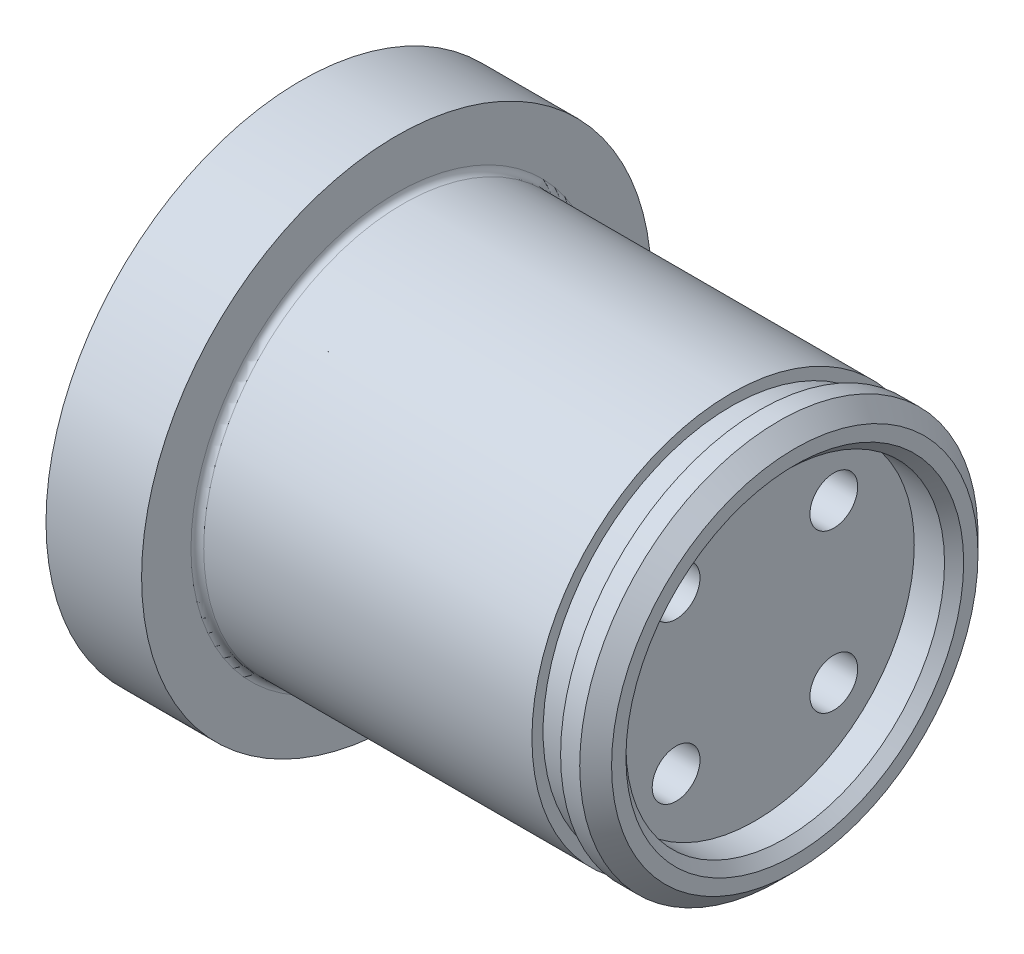
SolidWorks part; units mm, degrees
material "1060 Сплав"
ref_plane "Спереди" through (0, 0, 0) normal (0, 0, 1) x (1, 0, 0)
ref_plane "Сверху" through (0, 0, 0) normal (0, 1, 0) x (1, 0, 0)
ref_plane "Справа" through (0, 0, 0) normal (1, 0, 0) x (0, 0, -1)
sketch "Эскиз1" plane through (0, 0, 0) normal (0, 0, 1) x (1, 0, 0)
  line L0 (0, 0) -> (22138.4448, 0) construction
  line L1 (0, 0) -> (0, 12.5)
  line L2 (0, 12.5) -> (-25, 12.5)
  line L3 (-25, 12.5) -> (-25, 16)
  line L4 (-25, 16) -> (-31, 16)
  line L5 (-31, 16) -> (-31, 0)
  line L8 (0, 0) -> (-31, 0)
  dimension "D1" = 31
  dimension "D2" = 6
  dimension "D3" = 25
  dimension "D6" = 32
revolve "Повернуть1" add sketch "Эскиз1" angle 360 about L0
sketch "Эскиз2" plane through (0, 0, 0) normal (0, 0, 1) x (1, 0, 0)
  line L0 (-4, 12.5) -> (-4, 11.8)
  line L1 (0, 12.5) -> (-25, 12.5) construction
  line L2 (-4, 11.8) -> (-2.2, 11.8)
  line L3 (-2.2, 11.8) -> (-2.2, 12.5)
  line L4 (-2.2, 12.5) -> (-4, 12.5)
  line L5 (0, -12.5) -> (0, 12.5) construction
  line L6 (0, 0) -> (-50000, 0) construction
  point P10 (-2.2, 12.15)
  point P13 (0, 0)
  dimension "D1" = 4
  dimension "D2" = 1.8
  dimension "D3" = 23.6
revolve "Вырез-Повернуть1" cut sketch "Эскиз2" angle 360 about L6
chamfer "Фаска1" distance 1 angle 45 1 edges at (0, 0, 12.5)
fillet "Скругление1" radius 0.4 1 edges at (-25, 0, 12.5)
hole_wizard "Отверстие1" positions "Эскиз3" profile "Эскиз4" legacy end condition through all
sketch "Эскиз3" plane through (0, 0, 0) normal (1, 0, 0) x (0, 0, -1)
  line L0 (0, 0) -> (0, 7) construction
  line L2 (0, 0) -> (4.9497, 4.9497) construction
  circle A0 centre (0, 0) radius 7 construction
  point P0 (4.9497, 4.9497)
  dimension "D1" = 14
  dimension "D2" = 45
sketch "Эскиз4" plane through (0, 4.9497, -4.9497) normal (0, 1, 0) x (0, 0, -1)
  line L0 (0, 0) -> (0, 31)
  line L1 (0, 31) -> (1.5, 31)
  line L2 (1.5, 31) -> (1.5, 0)
  line L3 (1.5, 0) -> (0, 0)
  line L4 (0, 110) -> (0, -10) construction
  dimension "Диаметр" = 3
  dimension "Глубина" = 31
pattern_circular "Круговой массив1" count 4 over 360 about axis through (0, 0, 0) along (1, 0, 0) of "Отверстие1"
sketch "Эскиз5" plane through (0, 0, 0) normal (0, 0, 1) x (1, 0, 0)
  line L0 (0, 0) -> (0, 10)
  line L1 (0, -11.5) -> (0, 11.5) construction
  line L7 (0, 10) -> (-2.5, 10)
  line L8 (-2.5, 10) -> (-2.5, 0)
  line L9 (-2.5, 0) -> (0, 0)
  line L10 (0, 0) -> (-50000, 0) construction
  dimension "D1" = 2.5
  dimension "D2" = 20
revolve "Вырез-Повернуть2" cut sketch "Эскиз5" angle 360 about L10
chamfer "Фаска2" distance 0.6 angle 45 1 edges at (0, 0, -10)
